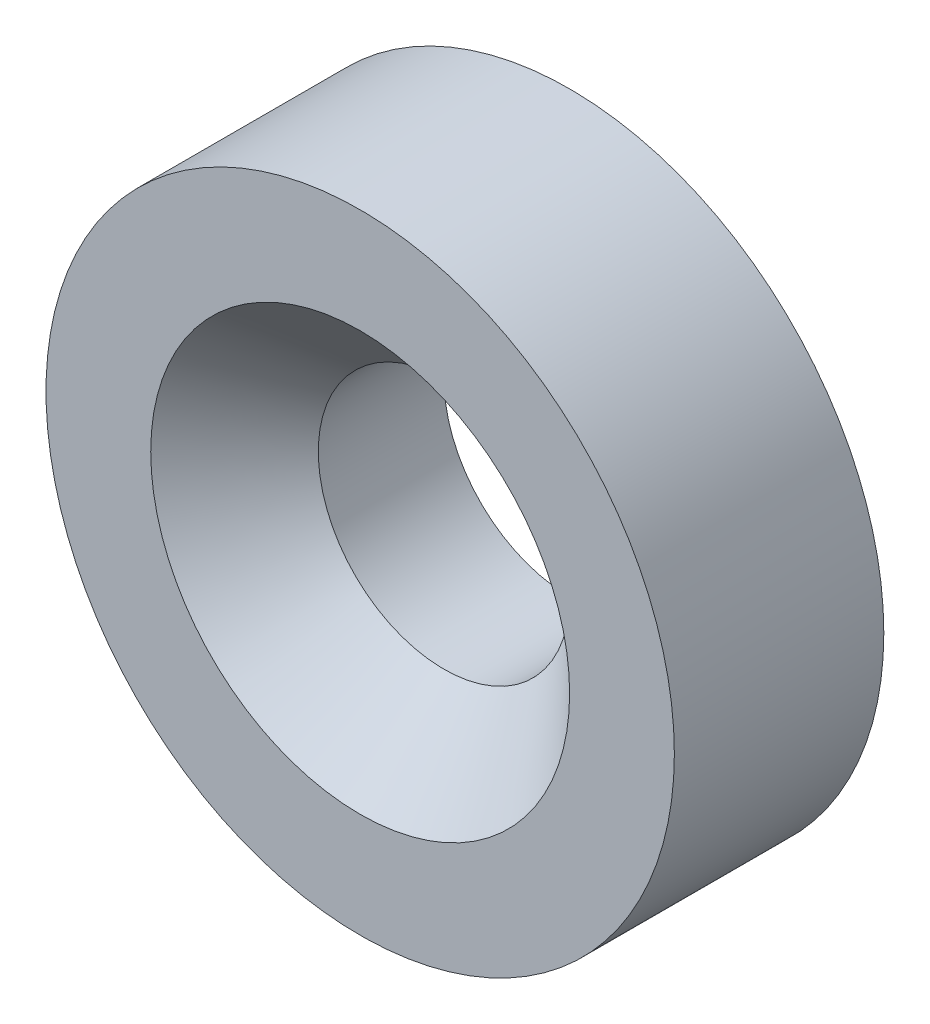
SolidWorks part; units mm, degrees
ref_plane "Front Plane" through (0, 0, 0) normal (0, 0, 1) x (1, 0, 0)
ref_plane "Top Plane" through (0, 0, 0) normal (0, 1, 0) x (1, 0, 0)
ref_plane "Right Plane" through (0, 0, 0) normal (1, 0, 0) x (0, 0, -1)
sketch "Sketch1" plane through (0, 0, 0) normal (0, 0, 1) x (1, 0, 0)
  circle A0 centre (0, 0) radius 0.75
  dimension "D1" = 1.5
extrude "Boss-Extrude1" add sketch "Sketch1" along normal blind 0.5
sketch "Sketch2" plane through (0, 0, 0.5) normal (0, 0, 1) x (1, 0, 0)
  circle A0 centre (0, 0) radius 0.3
  dimension "D1" = 0.6
extrude "Cut-Extrude1" cut sketch "Sketch2" against normal through all
chamfer "Chamfer1" distance 0.2 angle 45 1 edges at (0.3, 0, 0.5)
